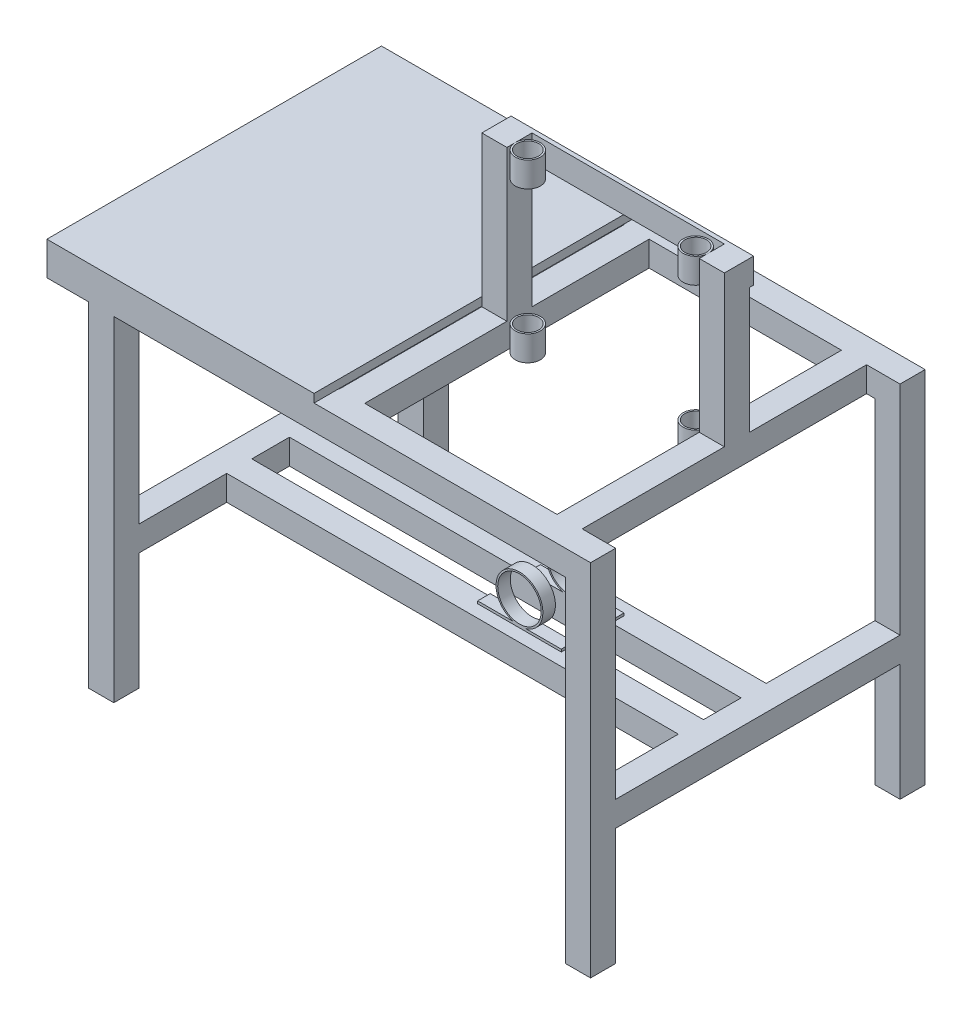
SolidWorks part; units mm, degrees
ref_plane "Front Plane" through (0, 0, 0) normal (0, 0, 1) x (1, 0, 0)
ref_plane "Top Plane" through (0, 0, 0) normal (0, 1, 0) x (1, 0, 0)
ref_plane "Right Plane" through (0, 0, 0) normal (1, 0, 0) x (0, 0, -1)
sketch "Sketch4" plane through (0, 0, 0) normal (0, 1, 0) x (1, 0, 0)
  line L0 (-270, 170) -> (270, 170)
  line L1 (-300, -200) -> (300, -200)
  line L2 (-300, -200) -> (-300, 200)
  line L3 (-300, 200) -> (300, 200)
  line L4 (300, -200) -> (300, 200)
  line L5 (-300, -200) -> (300, 200) construction
  line L6 (-300, 200) -> (300, -200) construction
  line L7 (270, -170) -> (270, 170)
  line L8 (-270, -170) -> (270, -170)
  line L9 (-270, -170) -> (-270, 170)
  point P0 (0, 0)
  dimension "D2" = 400
  dimension "D3" = 600
  dimension "D1" = 30
extrude "Boss-Extrude2" add sketch "Sketch4" along normal blind 30
sketch "Sketch10" plane through (0, 0, 200) normal (0, 0, 1) x (1, 0, 0)
  line L0 (-300, 30) -> (300, 30) construction
  line L1 (-30, 30) -> (0, 30)
  line L2 (-30, 30) -> (-30, 0)
  line L3 (-30, 0) -> (0, 0)
  line L4 (0, 30) -> (0, 0)
  line L5 (-300, 0) -> (300, 0) construction
  dimension "D1" = 30
  dimension "D2" = 300
extrude "Boss-Extrude7" add sketch "Sketch10" against normal up to surface (370 mm away) up to face at (0, 15, -170)
sketch "Sketch17" plane through (0, 0, 0) normal (0, -1, 0) x (1, 0, 0)
  line L0 (300, 200) -> (300, -200) construction
  line L1 (-300, 200) -> (-270, 200)
  line L2 (-300, 200) -> (-300, 170)
  line L3 (-300, 170) -> (-270, 170)
  line L4 (-270, 200) -> (-270, 170)
  line L5 (300, 200) -> (270, 200)
  line L6 (300, 200) -> (300, 170)
  line L7 (300, 170) -> (270, 170)
  line L8 (270, 200) -> (270, 170)
  line L9 (-300, 200) -> (300, 200) construction
  line L11 (300, -200) -> (270, -200)
  line L12 (300, -200) -> (300, -170)
  line L13 (300, -170) -> (270, -170)
  line L14 (270, -200) -> (270, -170)
  line L15 (-300, -200) -> (-270, -200)
  line L16 (-300, -200) -> (-300, -170)
  line L17 (-300, -170) -> (-270, -170)
  line L18 (-270, -200) -> (-270, -170)
extrude "Boss-Extrude13" add sketch "Sketch17" along normal blind 500
sketch "Sketch18" plane through (0, 0, 200) normal (0, 0, 1) x (1, 0, 0)
  line L0 (270, -500) -> (270, 0) construction
  line L1 (270, -230) -> (300, -230)
  line L2 (270, -230) -> (270, -260)
  line L3 (270, -260) -> (300, -260)
  line L4 (300, -230) -> (300, -260)
  line L5 (300, 30) -> (300, -500) construction
  line L6 (-300, 30) -> (-300, -500) construction
  line L7 (-300, -230) -> (-270, -230)
  line L8 (-300, -230) -> (-300, -260)
  line L9 (-300, -260) -> (-270, -260)
  line L10 (-270, -230) -> (-270, -260)
  line L11 (-270, -500) -> (-270, 0) construction
  line L12 (-270, 0) -> (270, 0) construction
  dimension "D1" = 30
  dimension "D2" = 230
  dimension "D3" = 230
extrude "Boss-Extrude14" add sketch "Sketch18" against normal up to surface (370 mm away) up to face at (-285, -250, -170)
sketch "Sketch19" plane through (-300, 0, 0) normal (-1, 0, 0) x (0, 0, 1)
  line L0 (-170, -230) -> (170, -230) construction
  line L1 (-40, -230) -> (-10, -230)
  line L2 (-40, -230) -> (-40, -260)
  line L3 (-40, -260) -> (-10, -260)
  line L4 (-10, -230) -> (-10, -260)
  line L5 (-170, -260) -> (170, -260) construction
  line L6 (170, -230) -> (170, 0) construction
  line L7 (35, -230) -> (65, -230)
  line L8 (35, -230) -> (35, -260)
  line L9 (35, -260) -> (65, -260)
  line L10 (65, -230) -> (65, -260)
  dimension "D1" = 30
  dimension "D2" = 30
  dimension "D3" = 45
  dimension "D4" = 105
extrude "Boss-Extrude15" add sketch "Sketch19" against normal up to surface (570 mm away) up to face at (270, -248.3333, 0)
sketch "Sketch21" plane through (0, 0, -10) normal (0, 0, 1) x (1, 0, 0)
  line L0 (300, 30) -> (300, -500) construction
  line L1 (270, -230) -> (-270, -230) construction
  line L2 (72.4162, -227) -> (115, -227)
  line L3 (15, -233) -> (115, -233)
  line L4 (15, -233) -> (15, -227)
  line L5 (15, -227) -> (57.5838, -227)
  line L6 (115, -233) -> (115, -227)
  line L7 (15, -233) -> (115, -227) construction
  line L8 (15, -227) -> (115, -233) construction
  line L9 (270, -500) -> (270, 0) construction
  circle A0 centre (65, -200) radius 26
  arc A1 (72.4162, -227) -> (57.5838, -227) centre (65, -200) ccw
  circle A3 centre (65, -200) radius 28 construction
  point P8 (65, -230)
  point P13 (211.7765, -211.8136)
  dimension "D2" = 52
  dimension "D1" = 235
  dimension "D4" = 30
  dimension "D5" = 100
  dimension "D6" = 6
  dimension "D7" = 155
  dimension "D3" = 2
extrude "Boss-Extrude17" add sketch "Sketch21" against normal blind 15
sketch "Sketch22" plane through (0, 0, 35) normal (0, 0, -1) x (-1, 0, 0)
  line L0 (-57.5838, -227) -> (-15, -227)
  line L1 (-115, -227) -> (-72.4162, -227)
  line L2 (-115, -227) -> (-115, -230)
  line L3 (-115, -230) -> (-15, -230)
  line L4 (-15, -227) -> (-15, -230)
  circle A0 centre (-65, -200) radius 26
  arc A1 (-57.5838, -227) -> (-72.4162, -227) centre (-65, -200) ccw
  dimension "D1" = 28
extrude "Boss-Extrude18" add sketch "Sketch22" against normal blind 15
sketch "Sketch23" plane through (0, -500, 0) normal (0, -1, 0) x (1, 0, 0)
  line L0 (300, -200) -> (300, -170) construction
  line L1 (-300, 200) -> (-270, 200)
  line L2 (-300, 200) -> (-300, 170)
  line L3 (-300, 170) -> (-270, 170)
  line L4 (-270, 200) -> (-270, 170)
  line L5 (300, 200) -> (270, 200)
  line L6 (300, 200) -> (300, 170)
  line L7 (300, 170) -> (270, 170)
  line L8 (270, 200) -> (270, 170)
  line L9 (270, -170) -> (300, -170)
  line L10 (270, -170) -> (270, -200)
  line L11 (270, -200) -> (300, -200)
  line L12 (300, -170) -> (300, -200)
  line L13 (270, -200) -> (300, -200) construction
  line L15 (-300, -170) -> (-270, -170)
  line L16 (-300, -170) -> (-300, -200)
  line L17 (-300, -200) -> (-270, -200)
  line L18 (-270, -170) -> (-270, -200)
extrude "Cut-Extrude2" cut sketch "Sketch23" against normal blind 100
sketch "Sketch27" plane through (0, 0, -170) normal (0, 0, 1) x (1, 0, 0)
  line L0 (-300, 30) -> (300, 30) construction
  line L1 (230, 30) -> (260, 30)
  line L2 (230, 30) -> (230, 0)
  line L3 (230, 0) -> (260, 0)
  line L4 (260, 30) -> (260, 0)
  line L5 (-270, 0) -> (270, 0) construction
  dimension "D1" = 30
  dimension "D2" = 230
extrude "Boss-Extrude22" add sketch "Sketch27" along normal up to surface (340 mm away) up to face at (135, 15, 170)
sketch "Sketch28" plane through (0, 30, 0) normal (0, 1, 0) x (1, 0, 0)
  line L0 (-30, 170) -> (-30, -170) construction
  line L1 (0, 0) -> (-30, 0)
  line L2 (0, 0) -> (0, 30)
  line L3 (0, 30) -> (-30, 30)
  line L4 (-30, 0) -> (-30, 30)
  line L5 (230, -170) -> (230, 170) construction
  line L6 (230, 0) -> (260, 0)
  line L7 (230, 0) -> (230, 30)
  line L8 (230, 30) -> (260, 30)
  line L9 (260, 0) -> (260, 30)
  line L10 (260, -170) -> (260, 170) construction
  dimension "D1" = 30
  dimension "D2" = 30
extrude "Boss-Extrude23" add sketch "Sketch28" along normal blind 180
sketch "Sketch31" plane through (0, 0, 0) normal (0, -1, 0) x (1, 0, 0)
  line L0 (0, 0) -> (0, -30) construction
  line L1 (-30, 0) -> (0, 0) construction
  line L2 (230, 170) -> (230, 0) construction
  circle A0 centre (15, -10) radius 13
  circle A1 centre (15, -10) radius 15
  circle A2 centre (215, -10.6763) radius 13
  circle A3 centre (215, -10.6763) radius 15
  dimension "D1" = 15
  dimension "D3" = 15
  dimension "D2" = 10
extrude "Boss-Extrude24" add sketch "Sketch31" against normal blind 30 separate body
sketch "Sketch34" plane through (0, 210, 0) normal (0, 1, 0) x (1, 0, 0)
  circle A0 centre (15, 10) radius 15
  circle A1 centre (15, 10) radius 13
  circle A2 centre (215, 10.6763) radius 13
  circle A3 centre (215, 10.6763) radius 15
extrude "Boss-Extrude25" add sketch "Sketch34" against normal blind 30 separate body
sketch "Sketch35" plane through (0, 0, -170) normal (0, 0, 1) x (1, 0, 0)
  line L1 (300, 30) -> (270, 30)
  line L2 (300, 30) -> (300, 0)
  line L3 (300, 0) -> (270, 0)
  line L4 (270, 30) -> (270, 0)
extrude "Cut-Extrude3" cut sketch "Sketch35" along normal up to surface (340 mm away) up to face at (285, -330, 170)
sketch "Sketch36" plane through (0, 0, -170) normal (0, 0, 1) x (1, 0, 0)
  line L0 (-270, -400) -> (-270, 0) construction
  line L1 (-300, 30) -> (-270, 30)
  line L2 (-300, 30) -> (-300, 0)
  line L3 (-300, 0) -> (-270, 0)
  line L4 (-270, 30) -> (-270, 0)
  line L5 (-270, 0) -> (270, 0) construction
extrude "Cut-Extrude4" cut sketch "Sketch36" along normal up to surface (340 mm away) up to face at (-285, -347.5, 170)
sketch "Sketch37" plane through (-300, 0, 0) normal (-1, 0, 0) x (0, 0, 1)
  line L0 (170, -230) -> (170, 30) construction
  line L1 (-200, 30) -> (-170, 30)
  line L2 (-200, 30) -> (-200, 0)
  line L3 (-200, 0) -> (-170, 0)
  line L4 (-170, 30) -> (-170, 0)
  line L5 (200, 30) -> (170, 30)
  line L6 (200, 30) -> (200, 0)
  line L7 (200, 0) -> (170, 0)
  line L8 (170, 30) -> (170, 0)
  line L9 (170, 0) -> (170, 30) construction
extrude "Boss-Extrude26" add sketch "Sketch37" along normal blind 50
sketch "Sketch38" plane through (0, 0, -170) normal (0, 0, 1) x (1, 0, 0)
  line L0 (-350, 0) -> (-300, 0) construction
  line L1 (-350, 30) -> (-320, 30)
  line L2 (-350, 30) -> (-350, 0)
  line L3 (-350, 0) -> (-320, 0)
  line L4 (-320, 30) -> (-320, 0)
  dimension "D1" = 30
extrude "Boss-Extrude27" add sketch "Sketch38" along normal up to surface (340 mm away) up to face at (115, 15, 170)
sketch "Sketch39" plane through (0, 30, 0) normal (0, 1, 0) x (1, 0, 0)
  line L0 (-350, -200) -> (300, -200) construction
  line L1 (-350, 200) -> (-30.6039, 200)
  line L2 (-350, 200) -> (-350, -200)
  line L3 (-350, -200) -> (-30.6039, -200)
  line L4 (-30.6039, 200) -> (-30.6039, -200)
extrude "Boss-Extrude28" add sketch "Sketch39" along normal blind 10
sketch "Sketch42" plane through (0, 0, -30) normal (0, 0, -1) x (-1, 0, 0)
  line L0 (30, 210) -> (30, 30) construction
  line L1 (-260, 210) -> (30, 210)
  line L2 (-260, 210) -> (-260, 180)
  line L3 (-260, 180) -> (30, 180)
  line L4 (30, 210) -> (30, 180)
  dimension "D1" = 30
extrude "Boss-Extrude31" add sketch "Sketch42" along normal blind 5
